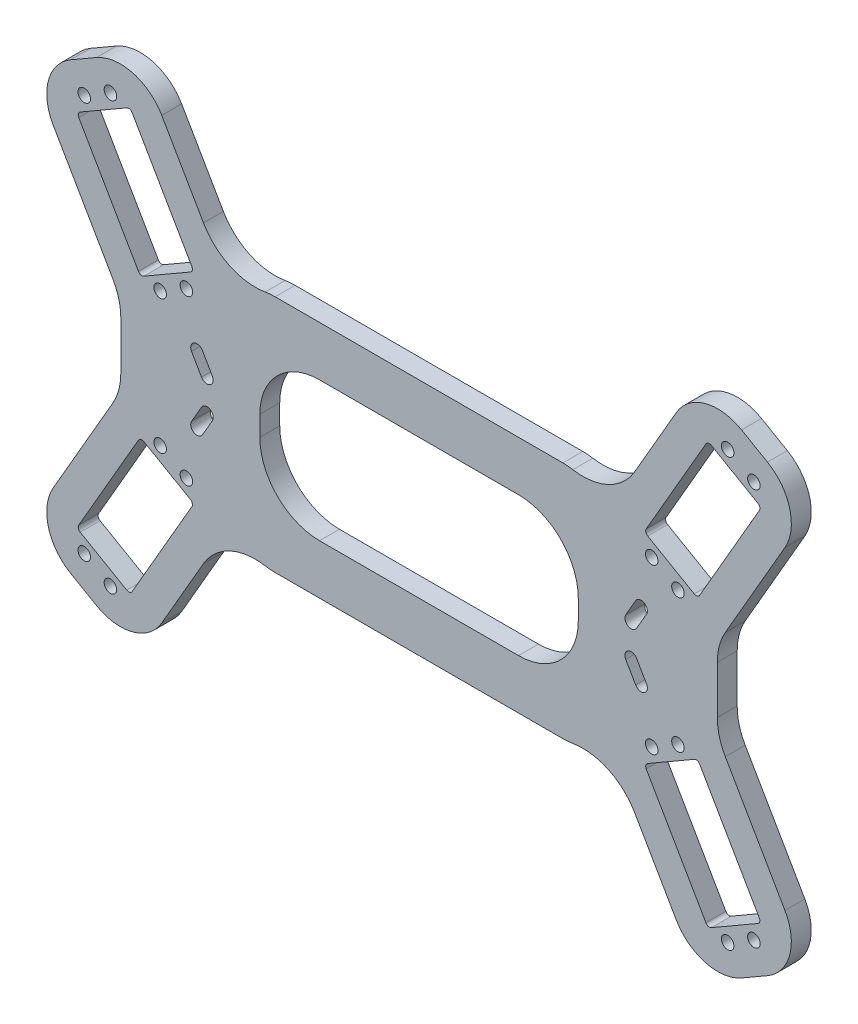
SolidWorks part; units mm, degrees
ref_plane "Plan de face" through (0, 0, 0) normal (0, 0, 1) x (1, 0, 0)
ref_plane "Plan de dessus" through (0, 0, 0) normal (0, 1, 0) x (1, 0, 0)
ref_plane "Plan de droite" through (0, 0, 0) normal (1, 0, 0) x (0, 0, -1)
sketch "Esquisse1" plane through (0, 0, 0) normal (0, 0, 1) x (1, 0, 0)
  line L0 (0, 0) -> (0, 57.7686) construction
  line L1 (88.9, -22.225) -> (-88.9, -22.225)
  line L2 (88.9, -22.225) -> (88.9, 22.225)
  line L3 (88.9, 22.225) -> (-88.9, 22.225)
  line L4 (-88.9, -22.225) -> (-88.9, 22.225)
  line L5 (88.9, -22.225) -> (-88.9, 22.225) construction
  line L6 (88.9, 22.225) -> (-88.9, -22.225) construction
  line L7 (50.8, -38.1) -> (-50.8, -38.1)
  line L8 (50.8, -38.1) -> (50.8, 38.1)
  line L9 (50.8, 38.1) -> (-50.8, 38.1)
  line L10 (-50.8, -38.1) -> (-50.8, 38.1)
  line L11 (50.8, -38.1) -> (-50.8, 38.1) construction
  line L12 (50.8, 38.1) -> (-50.8, -38.1) construction
  line L13 (0, 57.7686) -> (0, -55.8914) construction
  line L14 (-88.9, 22.225) -> (-71.8523, 32.0675)
  line L15 (-88.9, 22.225) -> (-109.22, 57.4203)
  line L16 (-71.8523, 32.0675) -> (-92.1723, 67.2628)
  line L17 (-109.22, 57.4203) -> (-92.1723, 67.2628)
  line L18 (-88.9, 0) -> (88.9, 0) construction
  line L19 (-124.3688, 63.3388) -> (-89.7235, 83.3413)
  line L20 (-124.3688, 63.3388) -> (-95.1588, 12.7456)
  line L21 (-89.7235, 83.3413) -> (-60.5135, 32.7481)
  line L22 (-95.1588, 12.7456) -> (-60.5135, 32.7481)
  line L23 (-95.1588, 12.7456) -> (-95.1588, -12.7456)
  line L24 (88.9, 22.225) -> (-88.9, -22.225) construction
  line L25 (-95.1588, -12.7456) -> (-60.5135, -32.7481)
  line L26 (-89.7235, -83.3413) -> (-60.5135, -32.7481)
  line L27 (-124.3688, -63.3388) -> (-95.1588, -12.7456)
  line L28 (-124.3688, -63.3388) -> (-89.7235, -83.3413)
  line L29 (-109.22, -57.4203) -> (-92.1723, -67.2628)
  line L30 (-71.8523, -32.0675) -> (-92.1723, -67.2628)
  line L31 (-88.9, -22.225) -> (-109.22, -57.4203)
  line L32 (-88.9, -22.225) -> (-71.8523, -32.0675)
  line L33 (88.9, -22.225) -> (-88.9, -22.225)
  line L34 (95.1588, 12.7456) -> (95.1588, -12.7456)
  line L35 (124.3688, -63.3388) -> (89.7235, -83.3413)
  line L36 (-88.9, 22.225) -> (88.9, -22.225) construction
  line L37 (-88.9, 22.225) -> (88.9, -22.225) construction
  line L38 (-88.9, -22.225) -> (88.9, 22.225) construction
  line L39 (-60.5135, 32.7481) -> (-50.8, 38.1)
  line L40 (88.9, -22.225) -> (71.8523, -32.0675)
  line L41 (88.9, -22.225) -> (109.22, -57.4203)
  line L42 (71.8523, -32.0675) -> (92.1723, -67.2628)
  line L43 (109.22, -57.4203) -> (92.1723, -67.2628)
  line L44 (124.3688, -63.3388) -> (95.1588, -12.7456)
  line L45 (89.7235, -83.3413) -> (60.5135, -32.7481)
  line L46 (95.1588, -12.7456) -> (60.5135, -32.7481)
  line L47 (50.8, 38.1) -> (60.5135, 32.7481)
  line L48 (95.1588, 12.7456) -> (60.5135, 32.7481)
  line L49 (89.7235, 83.3413) -> (60.5135, 32.7481)
  line L50 (124.3688, 63.3388) -> (95.1588, 12.7456)
  line L51 (124.3688, 63.3388) -> (89.7235, 83.3413)
  line L52 (109.22, 57.4203) -> (92.1723, 67.2628)
  line L53 (71.8523, 32.0675) -> (92.1723, 67.2628)
  line L54 (88.9, 22.225) -> (109.22, 57.4203)
  line L55 (88.9, 22.225) -> (71.8523, 32.0675)
  line L56 (88.9, -22.225) -> (88.9, 22.225)
  line L57 (60.5135, -32.7481) -> (50.8, -38.1)
  line L58 (-50.8, -38.1) -> (-60.5135, -32.7481)
  point P0 (0, 0)
  point P6 (0, 0)
  dimension "D5" = 12.7
  dimension "D6" = 10.16
  dimension "D1" = 60
  dimension "D2" = 40.64
  dimension "D3" = 19.685
  dimension "D4" = 44.45
  dimension "D7" = 10.16
  dimension "D8" = 5.08
  dimension "7" = 177.8
  dimension "D10" = 76.2
  dimension "D11" = 101.6
extrude "Boss.-Extru.1" add sketch "Esquisse1" along normal blind 6.35
sketch "Esquisse2" plane through (0, 0, 6.35) normal (0, 0, 1) x (1, 0, 0)
  line L0 (-82.6031, 21.3514) -> (-74.2442, 26.1774) construction
  line L2 (-88.9, 22.225) -> (-71.8523, 32.0675) construction
  line L3 (3.4925, 0) -> (-3.4925, 0) construction
  line L4 (-82.6031, -21.3514) -> (-74.2442, -26.1774) construction
  line L5 (0, -3.4925) -> (0, 3.4925) construction
  line L6 (82.6031, -21.3514) -> (74.2442, -26.1774) construction
  line L7 (82.6031, 21.3514) -> (74.2442, 26.1774) construction
  line L8 (-80.3761, 27.1463) -> (-78.4236, 23.7644) construction
  line L9 (-95.1588, 0) -> (95.1588, 0) construction
  line L10 (-95.1588, 12.7456) -> (-95.1588, -12.7456) construction
  line L11 (95.1588, 12.7456) -> (95.1588, -12.7456) construction
  line L12 (0, 38.1) -> (0, -38.1) construction
  line L13 (50.8, 38.1) -> (-50.8, 38.1) construction
  line L14 (50.8, -38.1) -> (-50.8, -38.1) construction
  line L15 (-82.0123, 49.6651) -> (-99.06, 39.8226) construction
  line L16 (-71.8523, 32.0675) -> (-92.1723, 67.2628) construction
  line L17 (-88.9, 22.225) -> (-109.22, 57.4203) construction
  line L18 (-100.6961, 62.3415) -> (-102.6486, 65.7234) construction
  line L19 (-106.8281, 63.3104) -> (-98.4692, 68.1364) construction
  line L20 (106.8281, 63.3104) -> (98.4692, 68.1364) construction
  line L21 (100.6961, 62.3415) -> (102.6486, 65.7234) construction
  line L22 (100.6961, -62.3415) -> (102.6486, -65.7234) construction
  line L23 (106.8281, -63.3104) -> (98.4692, -68.1364) construction
  line L24 (-106.8281, -63.3104) -> (-98.4692, -68.1364) construction
  line L25 (-100.6961, -62.3415) -> (-102.6486, -65.7234) construction
  line L26 (-80.3761, 27.1463) -> (-78.4236, 23.7644) construction
  line L27 (-78.4236, 23.7644) -> (-70.9371, 10.7973) construction
  line L28 (-70.8511, 10.6485) -> (-67.6761, 5.1492) construction
  line L29 (-69.1191, 11.6485) -> (-65.9441, 6.1492)
  line L30 (-72.5832, 9.6485) -> (-69.4082, 4.1492)
  line L31 (-70.8511, -10.6485) -> (-67.6761, -5.1492) construction
  line L32 (-69.1191, -11.6485) -> (-65.9441, -6.1492)
  line L33 (-72.5832, -9.6485) -> (-69.4082, -4.1492)
  line L34 (-78.4236, -23.7644) -> (-70.9371, -10.7973) construction
  line L35 (78.4236, -23.7644) -> (70.9371, -10.7973) construction
  line L36 (78.4236, 23.7644) -> (70.9371, 10.7973) construction
  line L37 (70.8511, -10.6485) -> (67.6761, -5.1492) construction
  line L38 (69.1191, -11.6485) -> (65.9441, -6.1492)
  line L39 (72.5832, -9.6485) -> (69.4082, -4.1492)
  line L40 (70.8511, 10.6485) -> (67.6761, 5.1492) construction
  line L41 (69.1191, 11.6485) -> (65.9441, 6.1492)
  line L42 (72.5832, 9.6485) -> (69.4082, 4.1492)
  circle A0 centre (-82.6031, 21.3514) radius 2
  circle A1 centre (-74.2442, 26.1774) radius 2
  circle A2 centre (-74.2442, -26.1774) radius 2
  circle A3 centre (-82.6031, -21.3514) radius 2
  circle A4 centre (82.6031, -21.3514) radius 2
  circle A5 centre (74.2442, -26.1774) radius 2
  circle A6 centre (74.2442, 26.1774) radius 2
  circle A7 centre (82.6031, 21.3514) radius 2
  circle A8 centre (-98.4692, 68.1364) radius 2
  circle A9 centre (-106.8281, 63.3104) radius 2
  circle A10 centre (106.8281, 63.3104) radius 2
  circle A11 centre (98.4692, 68.1364) radius 2
  circle A12 centre (98.4692, -68.1364) radius 2
  circle A13 centre (106.8281, -63.3104) radius 2
  circle A14 centre (-106.8281, -63.3104) radius 2
  circle A15 centre (-98.4692, -68.1364) radius 2
  arc A16 (-69.1191, 11.6485) -> (-72.5832, 9.6485) centre (-70.8511, 10.6485) ccw
  arc A17 (-69.4082, 4.1492) -> (-65.9441, 6.1492) centre (-67.6761, 5.1492) ccw
  arc A18 (-69.1191, -11.6485) -> (-72.5832, -9.6485) centre (-70.8511, -10.6485) cw
  arc A19 (-69.4082, -4.1492) -> (-65.9441, -6.1492) centre (-67.6761, -5.1492) cw
  arc A20 (69.1191, -11.6485) -> (72.5832, -9.6485) centre (70.8511, -10.6485) ccw
  arc A21 (69.4082, -4.1492) -> (65.9441, -6.1492) centre (67.6761, -5.1492) ccw
  arc A22 (69.1191, 11.6485) -> (72.5832, 9.6485) centre (70.8511, 10.6485) cw
  arc A23 (69.4082, 4.1492) -> (65.9441, 6.1492) centre (67.6761, 5.1492) cw
  point P69 (-69.2636, 7.8988)
  point P76 (-69.2636, -7.8988)
  point P89 (69.2636, -7.8988)
  point P96 (69.2636, 7.8988)
  dimension "D1" = 4
  dimension "D2" = 4
  dimension "D6" = 2
  dimension "D3" = 9.652
  dimension "D4" = 90
  dimension "D5" = 3.905
  dimension "D7" = 6.35
  dimension "D8" = 19.05
extrude "Enlèv. mat.-Extru.1" cut sketch "Esquisse2" against normal blind 6.35
fillet "Congé1" radius 19.05 4 edges at (50.8, 22.225, 3.175) (50.8, -22.225, 3.175) (-50.8, -22.225, 3.175) (-50.8, 22.225, 3.175)
fillet "Congé2" radius 19.05 8 edges at (95.1588, -12.7456, 3.175) (95.1588, 12.7456, 3.175) (50.8, -38.1, 3.175) (-50.8, -38.1, 3.175) (50.8, 38.1, 3.175) (-50.8, 38.1, 3.175) (-95.1588, -12.7456, 3.175) (-95.1588, 12.7456, 3.175)
fillet "Congé3" radius 19.05 4 edges at (60.5135, 32.7481, 3.175) (-60.5135, 32.7481, 3.175) (-60.5135, -32.7481, 3.175) (60.5135, -32.7481, 3.175)
fillet "Congé4" radius 1.27 16 edges at (-109.22, 57.4203, 3.175) (-92.1723, 67.2628, 3.175) (-71.8523, 32.0675, 3.175) (-88.9, 22.225, 3.175) (-92.1723, -67.2628, 3.175) (-71.8523, -32.0675, 3.175) (-88.9, -22.225, 3.175) (-109.22, -57.4203, 3.175) (92.1723, -67.2628, 3.175) (71.8523, -32.0675, 3.175) (88.9, -22.225, 3.175) (109.22, -57.4203, 3.175) (109.22, 57.4203, 3.175) (92.1723, 67.2628, 3.175) (71.8523, 32.0675, 3.175) (88.9, 22.225, 3.175)
fillet "Congé5" radius 15.24 8 edges at (-124.3688, 63.3388, 3.175) (-89.7235, 83.3413, 3.175) (124.3688, 63.3388, 3.175) (89.7235, 83.3413, 3.175) (124.3688, -63.3388, 3.175) (89.7235, -83.3413, 3.175) (-89.7235, -83.3413, 3.175) (-124.3688, -63.3388, 3.175)
